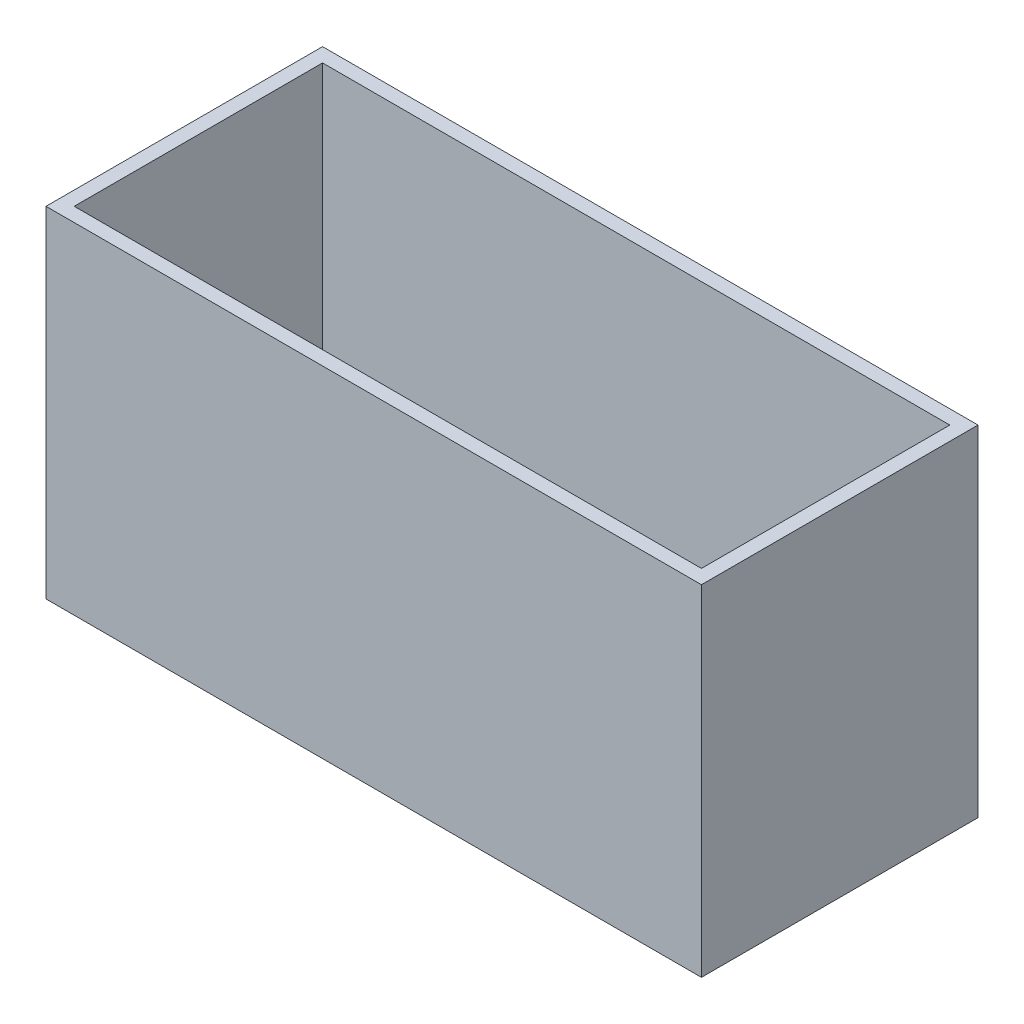
SolidWorks part; units mm, degrees
ref_plane "Front Plane" through (0, 0, 0) normal (0, 0, 1) x (1, 0, 0)
ref_plane "Top Plane" through (0, 0, 0) normal (0, 1, 0) x (1, 0, 0)
ref_plane "Right Plane" through (0, 0, 0) normal (1, 0, 0) x (0, 0, -1)
sketch "Sketch1" plane through (0, 0, 0) normal (0, 1, 0) x (1, 0, 0)
  line L1 (-464.5, -196) -> (464.5, -196)
  line L2 (-464.5, -196) -> (-464.5, 196)
  line L3 (-464.5, 196) -> (464.5, 196)
  line L4 (464.5, -196) -> (464.5, 196)
  line L5 (-464.5, -196) -> (464.5, 196) construction
  line L6 (-464.5, 196) -> (464.5, -196) construction
  point P0 (0, 0)
extrude "Bottom Plate" add sketch "Sketch1" along normal blind 20
sketch "Sketch2" plane through (0, 0, 0) normal (0, 1, 0) x (1, 0, 0)
  line L1 (-464.5, 176) -> (464.5, 176)
  line L2 (-464.5, 176) -> (-464.5, 196)
  line L3 (-464.5, 196) -> (464.5, 196)
  line L4 (464.5, 176) -> (464.5, 196)
  line L5 (-464.5, 176) -> (464.5, 196) construction
  line L6 (-464.5, 196) -> (464.5, 176) construction
  point P0 (0, 186)
extrude "Left Wall" add sketch "Sketch2" along normal blind 482
sketch "Sketch3" plane through (0, 0, 0) normal (0, 1, 0) x (1, 0, 0)
  line L0 (464.5, -196) -> (464.5, 176) construction
  line L1 (-464.5, -196) -> (464.5, -196)
  line L2 (-464.5, -196) -> (-464.5, -176)
  line L3 (-464.5, -176) -> (464.5, -176)
  line L4 (464.5, -196) -> (464.5, -176)
  line L5 (-464.5, -196) -> (464.5, -176) construction
  line L6 (-464.5, -176) -> (464.5, -196) construction
  point P0 (0, -186)
extrude "Right Wall" add sketch "Sketch3" along normal blind 482
sketch "Sketch4" plane through (0, 0, 0) normal (0, 1, 0) x (1, 0, 0)
  line L1 (444.5, -176) -> (464.5, -176)
  line L2 (444.5, -176) -> (444.5, 176)
  line L3 (444.5, 176) -> (464.5, 176)
  line L4 (464.5, -176) -> (464.5, 176)
  line L5 (444.5, -176) -> (464.5, 176) construction
  line L6 (444.5, 176) -> (464.5, -176) construction
  point P0 (454.5, 0)
extrude "Back Wall" add sketch "Sketch4" along normal blind 482
sketch "Sketch5" plane through (0, 0, 0) normal (0, 1, 0) x (1, 0, 0)
  line L0 (-464.5, 176) -> (444.5, 176) construction
  line L1 (-464.5, -176) -> (-444.5, -176)
  line L2 (-464.5, -176) -> (-464.5, 176)
  line L3 (-464.5, 176) -> (-444.5, 176)
  line L4 (-444.5, -176) -> (-444.5, 176)
  line L5 (-464.5, -176) -> (-444.5, 176) construction
  line L6 (-464.5, 176) -> (-444.5, -176) construction
  point P0 (-454.5, 0)
extrude "Front Wall" add sketch "Sketch5" along normal blind 482
